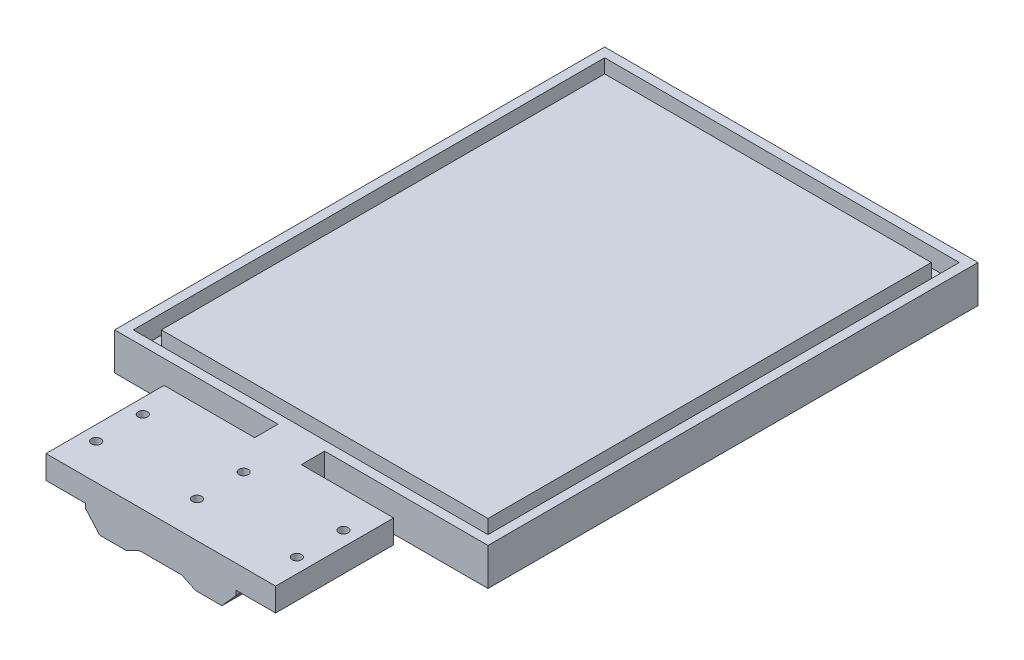
SolidWorks part; units mm, degrees
ref_plane "Front Plane" through (0, 0, 0) normal (0, 0, 1) x (1, 0, 0)
ref_plane "Top Plane" through (0, 0, 0) normal (0, 1, 0) x (1, 0, 0)
ref_plane "Right Plane" through (0, 0, 0) normal (1, 0, 0) x (0, 0, -1)
sketch "Sketch2" plane through (0, 0, 0) normal (0, 0, 1) x (1, 0, 0)
  line L0 (0, 11.8115) -> (0, -21.6138) construction
  line L1 (4.5, 3.4) -> (-4.5, 3.4)
  line L2 (-13.1, 2) -> (-7.5, 2)
  line L3 (-7.5, 2) -> (-4.5, 3.4)
  line L4 (-16.1, 6.4) -> (-24.6, 6.4)
  line L5 (-16.1, 5.4) -> (-13.1, 2)
  line L6 (-16.1, 5.4) -> (-16.1, 6.4)
  line L7 (-24.6, 6.4) -> (-24.6, 11.4)
  line L8 (-24.6, 11.4) -> (24.6, 11.4)
  line L9 (24.6, 6.4) -> (24.6, 11.4)
  line L10 (16.1, 5.4) -> (16.1, 6.4)
  line L11 (16.1, 5.4) -> (13.1, 2)
  line L12 (16.1, 6.4) -> (24.6, 6.4)
  line L13 (7.5, 2) -> (4.5, 3.4)
  line L14 (13.1, 2) -> (7.5, 2)
  point P13 (0, 11.4)
  point P19 (0, 3.4)
  dimension "D1" = 4.5
  dimension "D2" = 3.4
  dimension "D3" = 3
  dimension "D4" = 2
  dimension "D5" = 3
  dimension "D6" = 3.4
  dimension "D7" = 5.6
  dimension "D8" = 1
  dimension "D9" = 8.5
  dimension "D10" = 5
extrude "Boss-Extrude2" add sketch "Sketch2" along normal blind 25.3
sketch "Sketch3" plane through (0, 3.4, 0) normal (0, -1, 0) x (1, 0, 0)
  line L0 (0, 29.0012) -> (0, -6.3473) construction
  line L1 (-30.3292, 12.55) -> (30.8263, 12.55) construction
  line L4 (-24.6, 25.3) -> (-16.1, 25.3) construction
  circle A0 centre (0, 17.55) radius 1
  circle A1 centre (0, 7.55) radius 1
  dimension "D1" = 2
  dimension "D2" = 5
  dimension "D3" = 12.75
extrude "Cut-Extrude1" cut sketch "Sketch3" against normal through all
sketch "Sketch4" plane through (0, 6.4, 0) normal (0, -1, 0) x (1, 0, 0)
  line L0 (-21.5, 33.8063) -> (-21.5, -8.6098) construction
  line L1 (-35.4612, 12.65) -> (38.5522, 12.65) construction
  line L2 (-24.6, 25.3) -> (-16.1, 25.3) construction
  line L3 (-24.6, 25.3) -> (-24.6, 0) construction
  line L5 (0, 33.8063) -> (0, -8.6098) construction
  circle A0 centre (-21.5, 17.65) radius 1
  circle A3 centre (21.5, 17.65) radius 1
  circle A4 centre (-21.5, 7.65) radius 1
  circle A5 centre (21.5, 7.65) radius 1
  dimension "D1" = 2
  dimension "D2" = 5
  dimension "D5" = 2
  dimension "D6" = 10
  dimension "D3" = 12.65
  dimension "D4" = 3.1
extrude "Cut-Extrude2" cut sketch "Sketch4" against normal through all
sketch "Sketch5" plane through (0, 6.4, 0) normal (0, -1, 0) x (1, 0, 0)
  line L0 (-29.7281, 12.55) -> (31.1059, 12.55) construction
  line L1 (0, 33.5231) -> (0, -8.2392) construction
  line L4 (-24.6, 25.3) -> (-16.1, 25.3) construction
  circle A0 centre (-21.5, 17.65) radius 2.6
  circle A1 centre (-21.5, 7.45) radius 2.6
  circle A2 centre (21.5, 7.45) radius 2.6
  circle A3 centre (21.5, 17.65) radius 2.6
  dimension "D1" = 5.2
  dimension "D2" = 12.75
extrude "Cut-Extrude3" cut sketch "Sketch5" against normal blind 2
sketch "Sketch7" plane through (0, 0, 0) normal (0, 0, -1) x (-1, 0, 0)
  line L0 (-24.6, 11.4) -> (24.6, 11.4) construction
  line L1 (4.5, 3.4) -> (-4.5, 3.4) construction
  line L2 (-4.8083, 11.4) -> (5.1917, 11.4)
  line L3 (-4.8083, 11.4) -> (-4.8083, 3.4)
  line L4 (-4.8083, 3.4) -> (5.1917, 3.4)
  line L5 (5.1917, 11.4) -> (5.1917, 3.4)
extrude "Boss-Extrude4" add sketch "Sketch7" along normal blind 5
sketch "Sketch8" plane through (0, 0, -5) normal (0, 0, -1) x (-1, 0, 0)
  line L0 (0.1917, 30.5445) -> (0.1917, -7.7445) construction
  line L1 (5.1917, 11.4) -> (-4.8083, 11.4) construction
  line L2 (-24.6, 11.4) -> (-4.8083, 11.4) construction
  line L4 (-39.8083, 11.4) -> (40.1917, 11.4)
  line L5 (-39.8083, 11.4) -> (-39.8083, 3.4)
  line L6 (-39.8083, 3.4) -> (40.1917, 3.4)
  line L7 (40.1917, 11.4) -> (40.1917, 3.4)
  line L8 (-4.8083, 3.4) -> (5.1917, 3.4) construction
  point P4 (0.1917, 11.4)
  point P14 (0.1917, 11.4)
  dimension "D1" = 80
extrude "Boss-Extrude5" add sketch "Sketch8" along normal blind 105
sketch "Sketch9" plane through (0, 11.4, 0) normal (0, 1, 0) x (1, 0, 0)
  line L0 (34.8083, 10) -> (-35.1917, 10)
  line L1 (-35.1917, 105) -> (-35.1917, 10)
  line L2 (-35.1917, 105) -> (34.8083, 105)
  line L3 (37.8083, 7) -> (-38.1917, 7)
  line L4 (4.8083, 5) -> (39.8083, 5) construction
  line L5 (34.8083, 105) -> (34.8083, 10)
  line L6 (-38.1917, 108) -> (-38.1917, 7)
  line L7 (-38.1917, 108) -> (37.8083, 108)
  line L8 (37.8083, 108) -> (37.8083, 7)
  line L9 (-40.1917, 110) -> (39.8083, 110) construction
  line L10 (39.8083, 110) -> (39.8083, 5) construction
  line L11 (-40.1917, 110) -> (-40.1917, 5) construction
  dimension "D1" = 2
  dimension "D2" = 2
  dimension "D3" = 2
  dimension "D5" = 2
  dimension "D4" = 3
extrude "Cut-Extrude4" cut sketch "Sketch9" against normal blind 4
